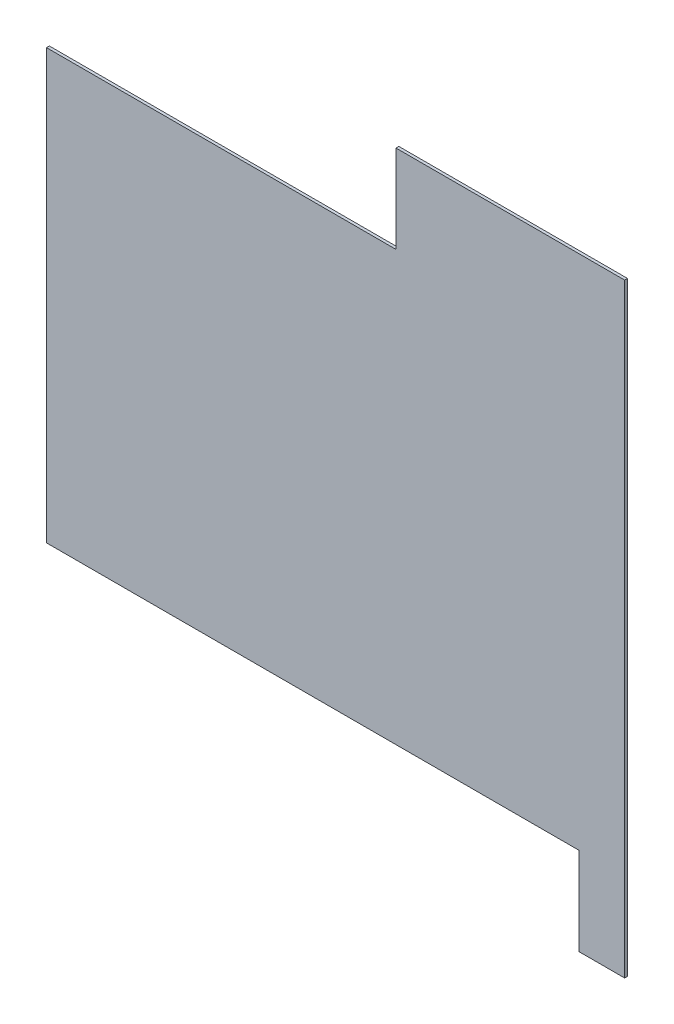
SolidWorks part; units mm, degrees
ref_plane "Front Plane" through (0, 0, 0) normal (0, 0, 1) x (1, 0, 0)
ref_plane "Top Plane" through (0, 0, 0) normal (0, 1, 0) x (1, 0, 0)
ref_plane "Right Plane" through (0, 0, 0) normal (1, 0, 0) x (0, 0, -1)
sketch "Sketch1" plane through (0, 0, 0) normal (0, 0, 1) x (1, 0, 0)
  line L1 (1230, 1510) -> (0, 1510)
  line L2 (1685, 0) -> (0, 0)
  line L3 (0, 1510) -> (0, 0)
  line L9 (1685, 0) -> (1685, -309)
  line L10 (1685, -309) -> (2035, -309)
  line L11 (2035, -309) -> (2035, 1819)
  line L12 (2035, 1819) -> (1230, 1819)
  line L13 (1230, 1819) -> (1230, 1510)
other "Pen Sketch1" parameters "D1"=69.7562, "D2"=44.2015, "D3"=1675.8242, "D4"=1144.478, "D5"=271.6371, "D6"=2110
extrude "Boss-Extrude1" add sketch "Sketch1" along normal blind 10
extrude "Cut-Extrude2" cut sketch "Sketch3" against normal blind 330
sketch "Sketch3" plane through (-124.1121, -342, 1004.4575) normal (0, -1, 0) x (-1, 0, 0)
  line L1 (-1887.1121, 819.4575) -> (-1466.1121, 819.4575)
  line L2 (-1987.1121, 919.4575) -> (-1987.1121, 2569.4575)
  line L3 (-1887.1121, 2669.4575) -> (-1466.1121, 2669.4575)
  line L4 (-1366.1121, 919.4575) -> (-1366.1121, 2569.4575)
  arc A0 (-1466.1121, 819.4575) -> (-1366.1121, 919.4575) centre (-1466.1121, 919.4575) ccw
  arc A1 (-1887.1121, 819.4575) -> (-1987.1121, 919.4575) centre (-1887.1121, 919.4575) cw
  arc A2 (-1466.1121, 2669.4575) -> (-1366.1121, 2569.4575) centre (-1466.1121, 2569.4575) cw
  arc A3 (-1987.1121, 2569.4575) -> (-1887.1121, 2669.4575) centre (-1887.1121, 2569.4575) cw
sketch "Sketch4" plane through (0, 0, 0) normal (0, 0, -1) x (-1, 0, 0)
  line L0 (0, 0) -> (-1685, 0) construction
  line L1 (-1685, -12) -> (-1863, -12)
  line L2 (-1685, -12) -> (-1685, 0)
  line L3 (-1685, 0) -> (-1863, 0)
  line L4 (-1863, -12) -> (-1863, 0)
  line L5 (-1863, -309) -> (-1863, -12) construction
extrude "Cut-Extrude3" cut sketch "Sketch4" against normal through all
sketch "Sketch5" plane through (0, 0, 0) normal (0, 0, -1) x (-1, 0, 0)
  line L0 (-1863, -309) -> (-2035, -309) construction
  line L1 (-1863, 0) -> (-1875, 0)
  line L2 (-1863, 0) -> (-1863, -309)
  line L3 (-1863, -309) -> (-1875, -309)
  line L4 (-1875, 0) -> (-1875, -309)
  dimension "D1" = 12
extrude "Cut-Extrude4" cut sketch "Sketch5" against normal blind 10 contours L1 L4 L3 L2
